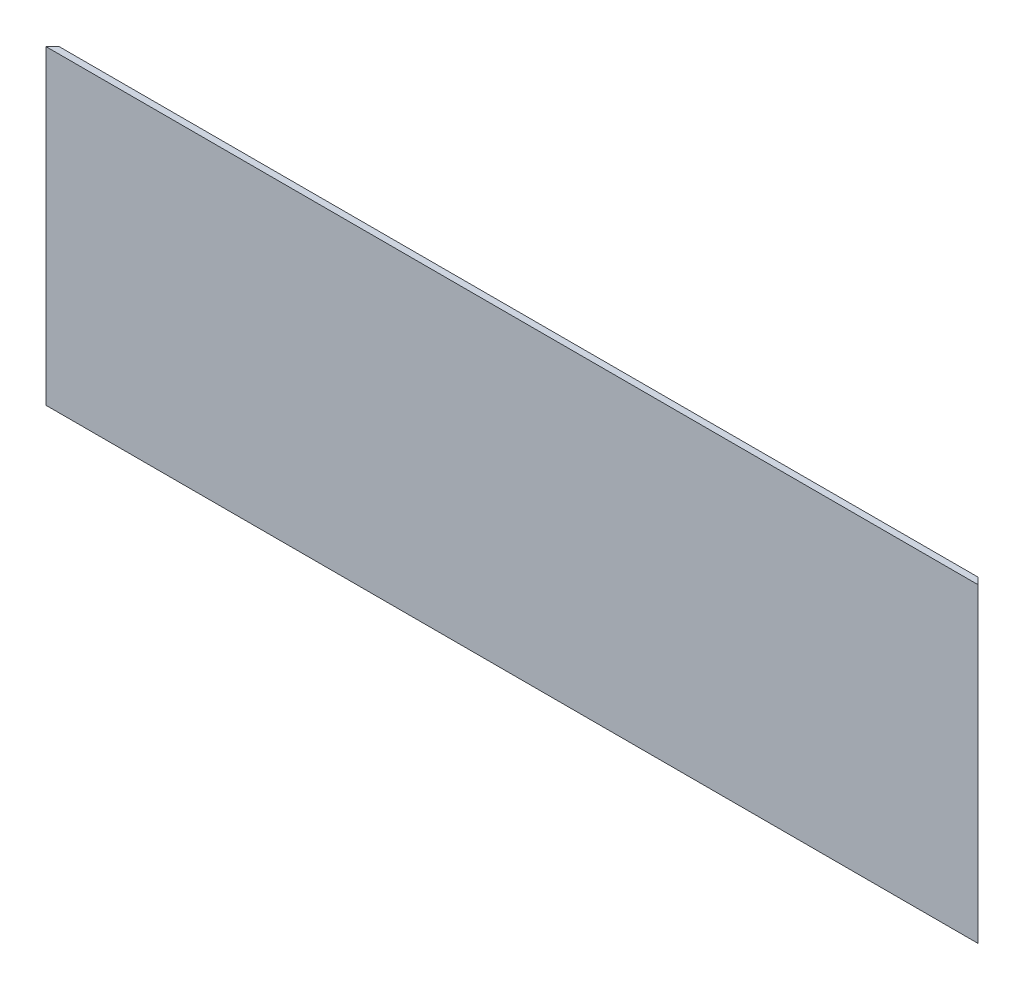
SolidWorks part; units mm, degrees
ref_plane "Front Plane" through (0, 0, 0) normal (0, 0, 1) x (1, 0, 0)
ref_plane "Top Plane" through (0, 0, 0) normal (0, 1, 0) x (1, 0, 0)
ref_plane "Right Plane" through (0, 0, 0) normal (1, 0, 0) x (0, 0, -1)
sketch "Sketch1" plane through (0, 0, 0) normal (0, 0, 1) x (1, 0, 0)
  line L1 (0, 0) -> (450, 0)
  line L2 (0, 0) -> (0, 150)
  line L3 (0, 150) -> (450, 150)
  line L4 (450, 0) -> (450, 150)
  dimension "D1" = 450
  dimension "D2" = 150
extrude "Boss-Extrude1" add sketch "Sketch1" along normal blind 3.175
sketch "Sketch2" plane through (0, 150, 0) normal (0, 1, 0) x (1, 0, 0)
  line L0 (0, -3.175) -> (3.175, 0)
  line L1 (450, 0) -> (0, 0) construction
  line L2 (3.175, 0) -> (0, 0)
  line L3 (0, 0) -> (0, -3.175)
  line L4 (450, -3.175) -> (446.825, 0)
  line L5 (446.825, 0) -> (450, 0)
  line L6 (450, 0) -> (450, -3.175)
extrude "Cut-Extrude1" cut sketch "Sketch2" against normal through all
